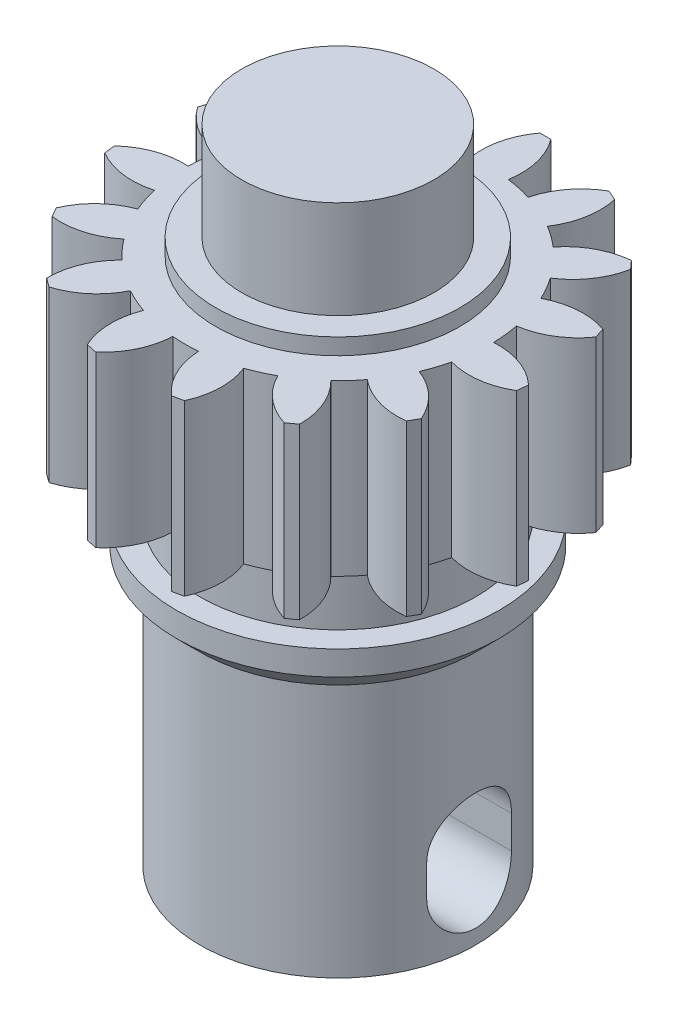
SolidWorks part; units mm, degrees
ref_plane "Plano frontal" through (0, 0, 0) normal (0, 0, 1) x (1, 0, 0)
ref_plane "Plano superior" through (0, 0, 0) normal (0, 1, 0) x (1, 0, 0)
ref_plane "Plano direito" through (0, 0, 0) normal (1, 0, 0) x (0, 0, -1)
sketch "Esboço1" plane through (0, 0, 0) normal (0, 0, 1) x (1, 0, 0)
  line L0 (0, 0) -> (0, 39.4)
  line L1 (0, 0) -> (8.47, 0)
  line L2 (8.47, 0) -> (8.47, 15.58)
  line L3 (8.47, 15.58) -> (9.9, 17.01)
  line L4 (9.9, 17.01) -> (9.9, 18.51)
  line L5 (9.9, 18.51) -> (8.47, 18.51)
  line L6 (8.47, 18.51) -> (8.47, 22)
  line L7 (8.47, 22) -> (9.374, 22)
  line L8 (9.374, 22) -> (9.374, 32.4)
  line L9 (9.374, 32.4) -> (7.5, 32.4)
  line L10 (7.5, 32.4) -> (7.5, 33.4)
  line L11 (7.5, 33.4) -> (5.9, 33.4)
  line L12 (5.9, 33.4) -> (5.9, 39.4)
  line L13 (5.9, 39.4) -> (0, 39.4)
  dimension "D1" = 8.47
  dimension "D2" = 22
  dimension "D3" = 3.49
  dimension "D4" = 1.5
  dimension "D5" = 135
  dimension "D6" = 9.9
  dimension "D7" = 9.374
  dimension "D8" = 7.5
  dimension "D9" = 10.4
  dimension "D10" = 1
  dimension "D11" = 6
  dimension "D12" = 5.9
revolve "Revolução1" add sketch "Esboço1" angle 360 about L0
sketch "Esboço2" plane through (0, 32.4, 0) normal (0, 1, 0) x (1, 0, 0)
  line L0 (-0.337, 12.746) -> (0.337, 12.746)
  line L1 (0, 0) -> (0, 0.674) construction
  line L2 (0, 0) -> (0, 12.746) construction
  line L3 (0, 0) -> (3.269, 10.0539) construction
  arc A1 (1.1676, 9.301) -> (-1.1676, 9.301) centre (0, 0) ccw
  arc A3 (0.337, 12.746) -> (1.1676, 9.301) centre (-3.269, 10.0539) cw
  arc A4 (-0.337, 12.746) -> (-1.1676, 9.301) centre (3.269, 10.0539) ccw
  point P3 (0, 12.746)
  dimension "D2" = 12.746
  dimension "D3" = 18.012
  dimension "D5" = 18.748
  dimension "D1" = 0.674
  dimension "D4" = 10.572
extrude "Ressalto-extrusão1" add sketch "Esboço2" against normal up to surface (10.4 mm away) up to face at (0, 22, -9.374)
pattern_circular "PadrãoCircular1" count 15 over 360 about axis through (0, 0, 0) along (0, 1, 0) of "Ressalto-extrusão1"
sketch "Esboço3" plane through (0, 0, 0) normal (0, -1, 0) x (1, 0, 0)
  circle A1 centre (0, 0) radius 3.3
  dimension "D1" = 6.6
extrude "Corte-extrusão1" cut sketch "Esboço3" against normal blind 22
sketch "Esboço4" plane through (0, 0, 0) normal (0, -1, 0) x (1, 0, 0)
  circle A0 centre (0, 0) radius 3.25
  dimension "D1" = 6.5
sketch "Esboço7" plane through (0, 0, 0) normal (1, 0, 0) x (0, 0, -1)
  line L0 (-2.6, 5.5) -> (2.6, 5.5) construction
  line L2 (-2.6, 5.5) -> (-2.6, 3.5)
  line L4 (2.6, 5.5) -> (2.6, 3.5)
  arc A0 (-2.6, 5.5) -> (2.6, 5.5) centre (0, 5.5) cw
  arc A1 (-2.6, 3.5) -> (2.6, 3.5) centre (0, 3.5) ccw
  dimension "D3" = 2.6
  dimension "D2" = 2
  dimension "D4" = 3.5
extrude "Corte-extrusão4" cut sketch "Esboço7" against normal mid plane 40
